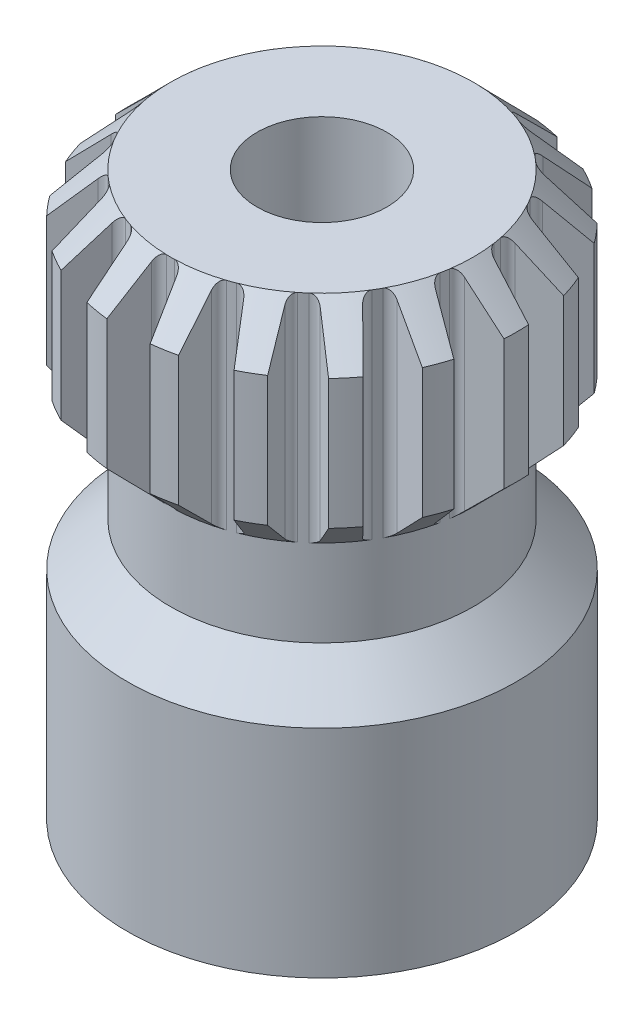
SolidWorks part; units mm, degrees
ref_plane "Front Plane" through (0, 0, 0) normal (0, 0, 1) x (1, 0, 0)
ref_plane "Top Plane" through (0, 0, 0) normal (0, 1, 0) x (1, 0, 0)
ref_plane "Right Plane" through (0, 0, 0) normal (1, 0, 0) x (0, 0, -1)
sketch "Sketch1" plane through (0, 0, 0) normal (0, 1, 0) x (1, 0, 0)
  circle A0 centre (0, 0) radius 2.25
  dimension "D1" = 4.5
extrude "Boss-Extrude1" add sketch "Sketch1" along normal blind 6.5
sketch "Sketch2" plane through (0, 0, 0) normal (0, 0, 1) x (1, 0, 0)
  line L0 (-2.25, 2.5) -> (-1.75, 3)
  line L1 (-2.25, 6.5) -> (-2.25, 0) construction
  line L2 (-1.75, 3) -> (-1.75, 4)
  line L4 (-2.25, 4) -> (-2.25, 2.5)
  line L5 (0, 0) -> (0, 7.5621) construction
  line L6 (-2.25, 6.5) -> (-2.25, 6)
  line L7 (-2.25, 6) -> (-1.75, 6.5)
  line L8 (2.25, 6.5) -> (-2.25, 6.5) construction
  line L9 (-1.75, 6.5) -> (-2.25, 6.5)
  line L10 (-1.75, 4) -> (-2.25, 4.5)
  line L11 (-2.25, 4.5) -> (-2.25, 4)
  dimension "D1" = 2.5
  dimension "D2" = 45
  dimension "D3" = 0.5
  dimension "D4" = 0.5
  dimension "D5" = 45
  dimension "D6" = 0.5
revolve "Cut-Revolve1" cut sketch "Sketch2" angle 360 about L5
sketch "Sketch3" plane through (0, 6.5, 0) normal (0, 1, 0) x (1, 0, 0)
  circle A0 centre (0, 0) radius 0.75
  dimension "D1" = 1.5
extrude "Cut-Extrude1" cut sketch "Sketch3" against normal through all
sketch "Sketch4" plane through (0, 6.5, 0) normal (0, 1, 0) x (1, 0, 0)
  line L0 (0, 0) -> (0, 2.6774) construction
  line L1 (-0.25, 2.2361) -> (-0.1452, 1.8247)
  line L2 (0.25, 2.2361) -> (0.1452, 1.8247)
  circle A0 centre (0, 0) radius 1.75 construction
  circle A1 centre (0, 0) radius 2.25 construction
  circle A2 centre (0, 0) radius 2.25 construction
  circle A3 centre (0, 0) radius 2 construction
  arc A4 (-0.0457, 1.7494) -> (0.0457, 1.7494) centre (0, 0) cw
  arc A5 (-0.25, 2.2361) -> (0.25, 2.2361) centre (0, 0) cw
  arc A6 (0.1452, 1.8247) -> (0.0457, 1.7494) centre (0.0483, 1.8494) cw
  arc A7 (-0.0457, 1.7494) -> (-0.1452, 1.8247) centre (-0.0483, 1.8494) cw
  point P15 (0.125, 1.7455)
  point P18 (-0.125, 1.7455)
  dimension "D1" = 0.5
  dimension "D2" = 0.25
  dimension "D5" = 0.1
  dimension "D3" = 0.5
  dimension "D4" = 0.25
extrude "Cut-Extrude2" cut sketch "Sketch4" against normal up to surface (2 mm away) up to face at (0, 4.5, -2.25)
pattern_circular "CirPattern1" count 18 over 360 about axis through (0, 0, 0) along (0, 1, 0) of "Cut-Extrude2"
